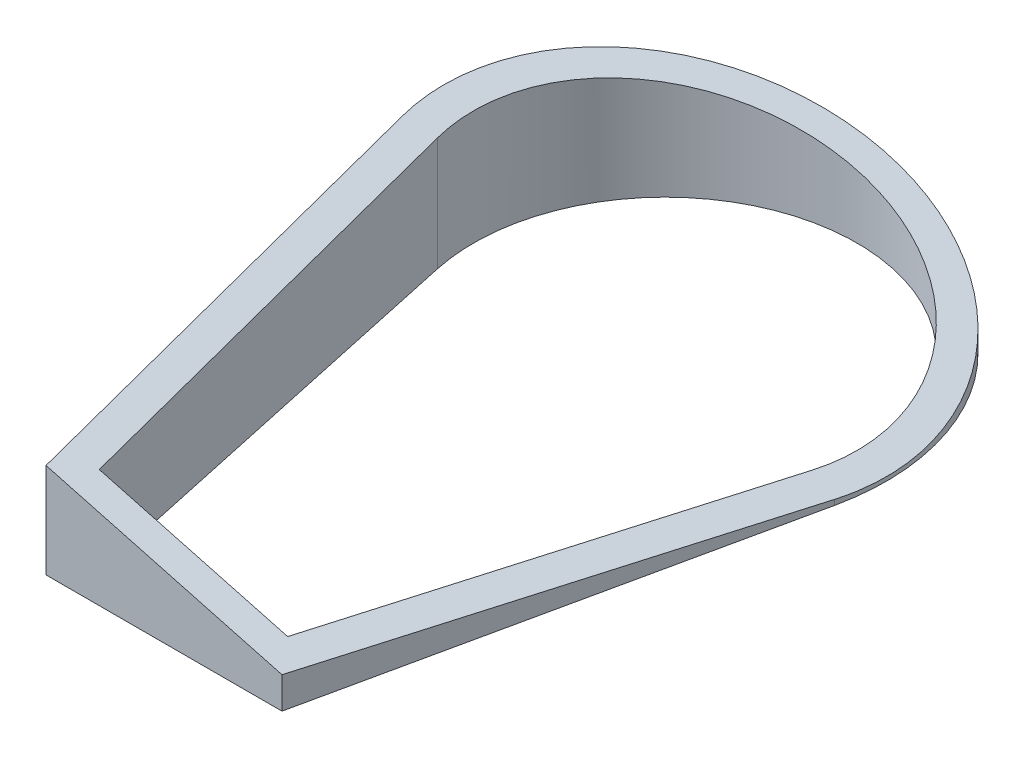
SolidWorks part; units mm, degrees
ref_plane "前视基准面" through (0, 0, 0) normal (0, 0, 1) x (1, 0, 0)
ref_plane "上视基准面" through (0, 0, 0) normal (0, 1, 0) x (1, 0, 0)
ref_plane "右视基准面" through (0, 0, 0) normal (1, 0, 0) x (0, 0, -1)
sketch "草图1" plane through (0, 0, 0) normal (0, 1, 0) x (1, 0, 0)
  line L0 (-73.31, -15.8317) -> (73.31, -15.8317) construction
  line L1 (0, 0) -> (-73.31, -15.8317) construction
  line L2 (0, 0) -> (73.31, -15.8317) construction
  line L3 (-73.31, -15.8317) -> (-40.0164, -170)
  line L4 (73.31, -15.8317) -> (40.0164, -170)
  line L5 (-40.0164, -170) -> (40.0164, -170)
  line L6 (-63.5353, -13.7208) -> (-31.9455, -160)
  line L7 (-31.9455, -160) -> (31.9455, -160)
  line L8 (63.5353, -13.7208) -> (31.9455, -160)
  arc A0 (73.31, -15.8317) -> (-73.31, -15.8317) centre (0, 0) ccw
  arc A1 (63.5353, -13.7208) -> (-63.5353, -13.7208) centre (0, 0) ccw
  point P1 (0, 0)
  point P7 (36.6325, -185.6697)
  dimension "D1" = 150
  dimension "D2" = 130
  dimension "D3" = 146.62
  dimension "D4" = 170
  dimension "D5" = 10
extrude "凸台-拉伸1" add sketch "草图1" along normal blind 70
sketch "草图2" plane through (0, 0, 170) normal (0, 0, 1) x (1, 0, 0)
  line L0 (-40.0164, 0) -> (40.0164, 0) construction
  line L1 (-80, 42.8719) -> (80, 0)
  line L2 (-80, 42.8719) -> (-80, 71.1755)
  line L3 (-80, 71.1755) -> (80, 71.1755)
  line L4 (80, 71.1755) -> (80, 0)
  line L5 (-80, 42.8719) -> (80, 42.8719) construction
  line L6 (-80, 42.8719) -> (-80, 0) construction
  line L7 (-80, 0) -> (80, 0) construction
  line L8 (80, 42.8719) -> (80, 0) construction
  dimension "D1" = 80
  dimension "D2" = 80
  dimension "D3" = 15
extrude "切除-拉伸1" cut sketch "草图2" against normal through all
